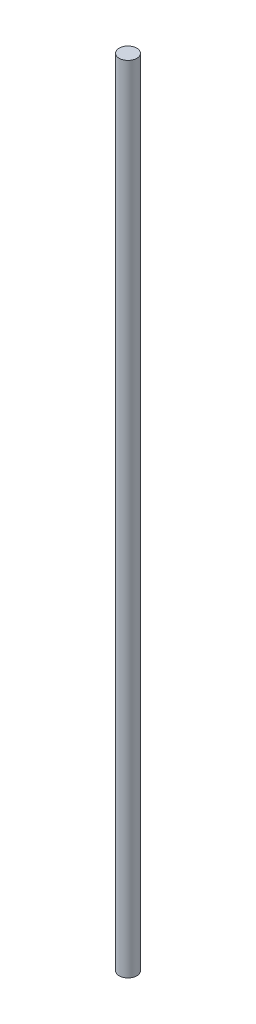
SolidWorks part; units mm, degrees
ref_plane "Płaszczyzna przednia" through (0, 0, 0) normal (0, 0, 1) x (1, 0, 0)
ref_plane "Płaszczyzna górna" through (0, 0, 0) normal (0, 1, 0) x (1, 0, 0)
ref_plane "Płaszczyzna prawa" through (0, 0, 0) normal (1, 0, 0) x (0, 0, -1)
sketch "Sketch1" plane through (0, 0, 0) normal (0, 1, 0) x (1, 0, 0)
  circle A0 centre (0, 0) radius 5
  point P3 (0, 0)
  dimension "D1" = 10
extrude "Boss-Extrude1" add sketch "Sketch1" along normal blind 450
